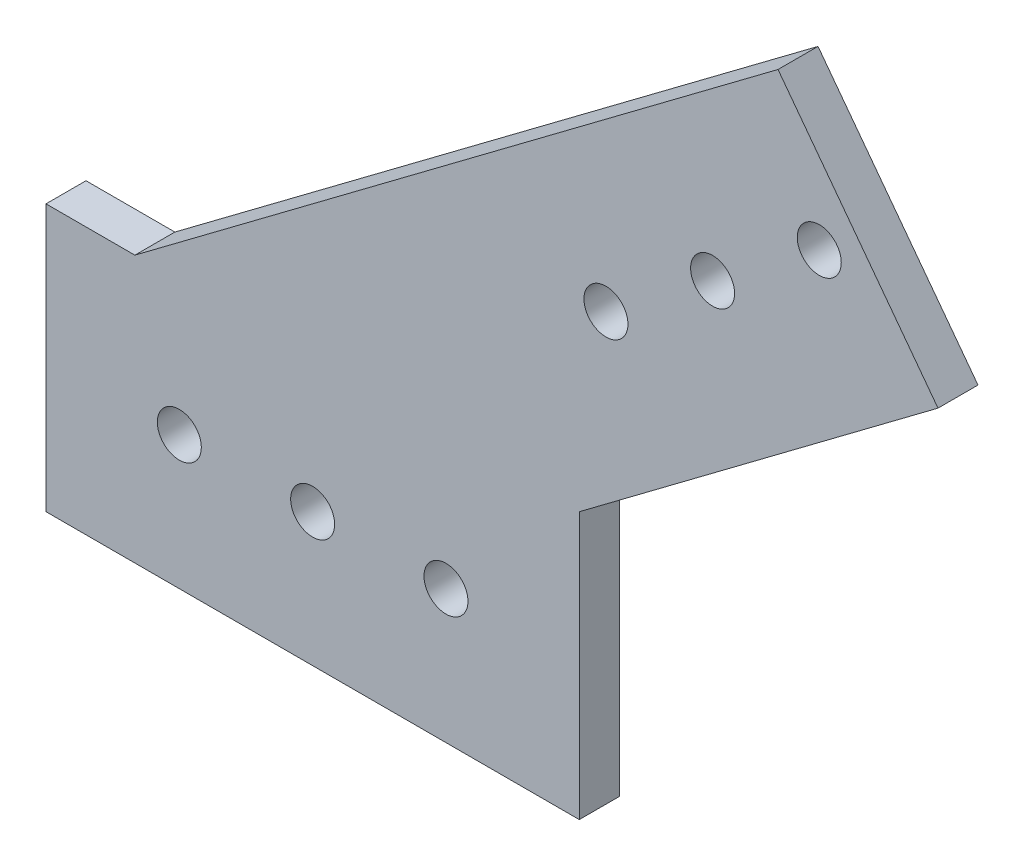
SolidWorks part; units mm, degrees
ref_plane "前视基准面" through (0, 0, 0) normal (0, 0, 1) x (1, 0, 0)
ref_plane "上视基准面" through (0, 0, 0) normal (0, 1, 0) x (1, 0, 0)
ref_plane "右视基准面" through (0, 0, 0) normal (1, 0, 0) x (0, 0, -1)
other "Configuration Table"
sketch "草图1" plane through (0, 0, 0) normal (0, 0, 1) x (1, 0, 0)
  line L0 (-41.667, -18.0623) -> (19.9323, -18.0623) construction
  line L1 (8.5026, -0.0623) -> (-15.4974, -18.0623) construction
  line L2 (-15.4974, -18.0623) -> (-5.4974, -18.0623) construction
  line L3 (-5.4974, -18.0623) -> (4.5026, -18.0623) construction
  line L4 (-18.8307, -8.0623) -> (-25.4974, -8.0623)
  line L5 (-25.4974, -8.0623) -> (-25.4974, -28.0623)
  line L6 (-25.4974, -28.0623) -> (14.5026, -28.0623)
  line L7 (14.5026, -28.0623) -> (14.5026, -8.0623)
  line L8 (8.5026, -0.0623) -> (32.5026, 17.9377) construction
  line L9 (-18.8307, -8.0623) -> (29.4088, 28.1174)
  line L10 (29.4088, 28.1174) -> (41.4089, 12.1174)
  line L11 (14.5026, -8.0623) -> (41.4089, 12.1174)
  line L12 (-18.8307, -8.0623) -> (14.5026, -8.0623) construction
  circle A0 centre (-5.4974, -18.0623) radius 1.65
  circle A1 centre (4.5026, -18.0623) radius 1.65
  circle A2 centre (-15.4974, -18.0623) radius 1.65
  circle A3 centre (16.5026, 5.9377) radius 1.65
  circle A4 centre (24.5026, 11.9377) radius 1.65
  circle A5 centre (32.5026, 17.9377) radius 1.65
  dimension "D1" = 10
  dimension "D2" = 10
  dimension "D3" = 10
  dimension "D4" = 10
  dimension "D5" = 10
  dimension "D6" = 10
  dimension "D7" = 20
  dimension "D8" = 10
extrude "凸台-拉伸1" add sketch "草图1" along normal blind 3
